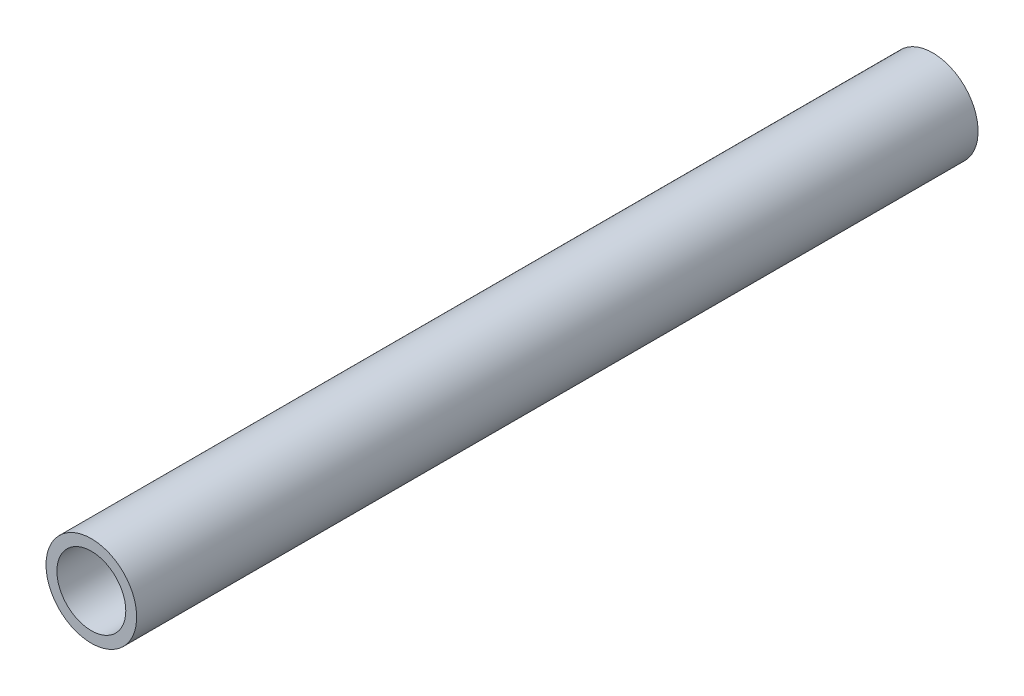
SolidWorks part; units mm, degrees
ref_plane "Front Plane" through (0, 0, 0) normal (0, 0, 1) x (1, 0, 0)
ref_plane "Top Plane" through (0, 0, 0) normal (0, 1, 0) x (1, 0, 0)
ref_plane "Right Plane" through (0, 0, 0) normal (1, 0, 0) x (0, 0, -1)
ref_plane "Plane1" through (0, 0, 230) normal (0, 0, 1) x (1, 0, 0)
sketch "Sketch1" plane through (0, 0, 230) normal (0, 0, 1) x (1, 0, 0)
  circle A0 centre (300, 300) radius 12.5
extrude "Boss-Extrude1" add sketch "Sketch1" along normal blind 232
sketch "Sketch2" plane through (0, 0, 462) normal (0, 0, 1) x (1, 0, 0)
  circle A0 centre (300, 300) radius 9.5
extrude "Cut-Extrude1" cut sketch "Sketch2" against normal blind 252
